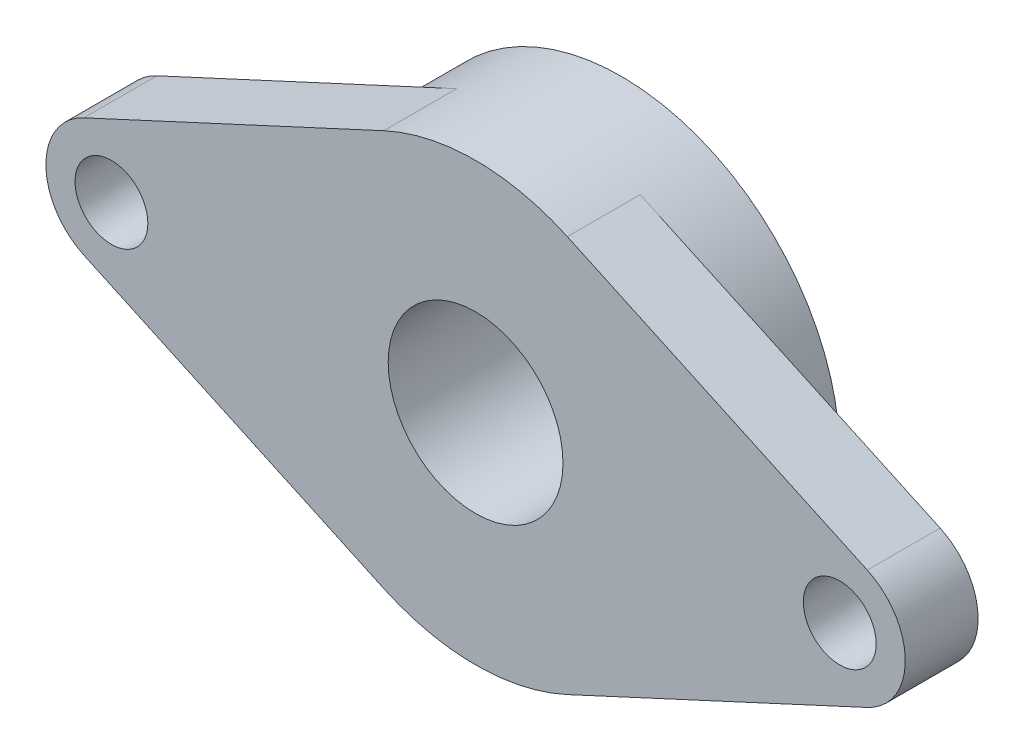
SolidWorks part; units mm, degrees
ref_plane "Front Plane" through (0, 0, 0) normal (0, 0, 1) x (1, 0, 0)
ref_plane "Top Plane" through (0, 0, 0) normal (0, 1, 0) x (1, 0, 0)
ref_plane "Right Plane" through (0, 0, 0) normal (1, 0, 0) x (0, 0, -1)
sketch "Sketch1" plane through (0, 0, 0) normal (0, 0, 1) x (1, 0, 0)
  line L0 (-27.5, 0) -> (56.6229, 0) construction
  line L1 (0, 26.1337) -> (0, -45.2983) construction
  line L2 (26.89, -4.0839) -> (6.3, -13.6129)
  line L3 (-26.89, -4.0839) -> (-6.3, -13.6129)
  line L4 (-26.89, 4.0839) -> (-6.3, 13.6129)
  line L5 (26.89, 4.0839) -> (6.3, 13.6129)
  circle A0 centre (0, 0) radius 6
  circle A1 centre (0, 0) radius 15
  circle A2 centre (-25, 0) radius 2.5
  circle A3 centre (25, 0) radius 2.5
  circle A4 centre (25, 0) radius 4.5
  circle A5 centre (-25, 0) radius 4.5
  dimension "D1" = 12
  dimension "D2" = 30
  dimension "D3" = 5
  dimension "D4" = 25
  dimension "D5" = 2
extrude "Boss-Extrude1" add sketch "Sketch1" along normal blind 5
sketch "Sketch2" plane through (0, 0, 0) normal (0, 0, -1) x (-1, 0, 0)
  circle A0 centre (0, 0) radius 15
  circle A1 centre (0, 0) radius 6
extrude "Boss-Extrude2" add sketch "Sketch2" along normal blind 5
